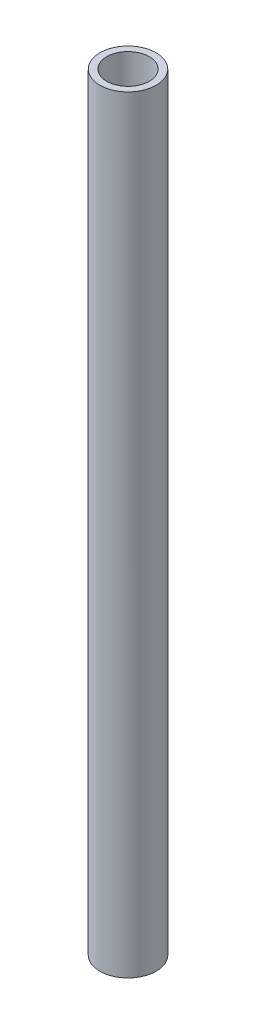
SolidWorks part; units mm, degrees
ref_plane "Front Plane" through (0, 0, 0) normal (0, 0, 1) x (1, 0, 0)
ref_plane "Top Plane" through (0, 0, 0) normal (0, 1, 0) x (1, 0, 0)
ref_plane "Right Plane" through (0, 0, 0) normal (1, 0, 0) x (0, 0, -1)
sketch "Sketch1" plane through (0, 0, 0) normal (0, 1, 0) x (1, 0, 0)
  circle A0 centre (0, 0) radius 8.382
  circle A1 centre (0, 0) radius 6.35
extrude "Boss-Extrude1" add sketch "Sketch1" along normal blind 228.6
sketch "Sketch3" plane through (0, 0, 0) normal (1, 0, 0) x (0, 0, -1)
  line L0 (0, -8.0951) -> (0, 43.2806) construction
  line L1 (-2.4177, -8.0951) -> (-2.4177, 43.2806)
  line L2 (2.4177, -8.0951) -> (2.4177, 43.2806)
  arc A0 (-2.4177, -8.0951) -> (2.4177, -8.0951) centre (0, -8.0951) ccw
  arc A1 (2.4177, 43.2806) -> (-2.4177, 43.2806) centre (0, 43.2806) ccw
  point P3 (0, 17.5927)
extrude "Cut-Extrude1" cut sketch "Sketch3" against normal blind 228.6
